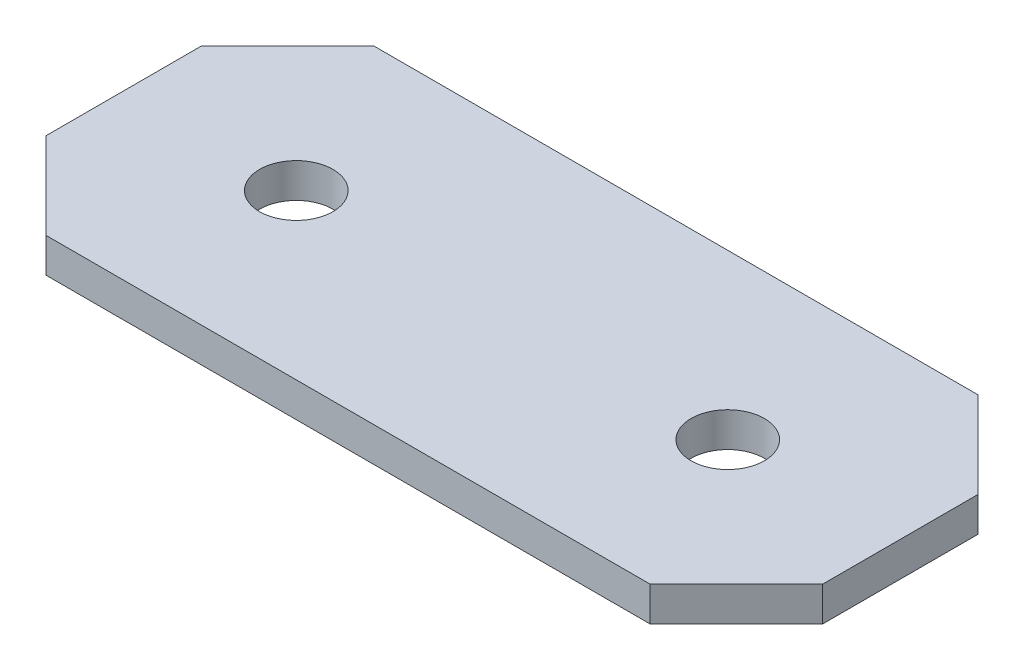
SolidWorks part; units mm, degrees
ref_plane "Płaszczyzna przednia" through (0, 0, 0) normal (0, 0, 1) x (1, 0, 0)
ref_plane "Płaszczyzna górna" through (0, 0, 0) normal (0, 1, 0) x (1, 0, 0)
ref_plane "Płaszczyzna prawa" through (0, 0, 0) normal (1, 0, 0) x (0, 0, -1)
sketch "Szkic1" plane through (0, 0, 0) normal (0, 1, 0) x (1, 0, 0)
  line L0 (-34.674, 0) -> (46.36, 0) construction
  line L1 (45, -9) -> (45, 9)
  line L2 (35, 19) -> (-35, 19)
  line L3 (0, 22.1971) -> (0, -30.5734) construction
  line L4 (35, -19) -> (-35, -19)
  line L5 (-45, -9) -> (-45, 9)
  line L6 (-35, 19) -> (-45, 9)
  line L7 (45, 9) -> (35, 19)
  line L8 (-35, -19) -> (-45, -9)
  line L9 (35, -19) -> (45, -9)
  circle A0 centre (25, 0) radius 4.25
  circle A1 centre (-25, 0) radius 4.25
  point P1 (-45, 19)
  point P4 (45, 19)
  point P10 (45, -19)
  point P11 (35, 0)
  point P12 (-45, -19)
  point P13 (0, -19)
  point P14 (0, 19)
  dimension "D3" = 25
  dimension "D4" = 8.5
  dimension "D9" = 25
  dimension "D10" = 8.5
  dimension "D1" = 90
  dimension "D2" = 38
extrude "Dodanie-wyciągnięcie1" add sketch "Szkic1" along normal blind 4
